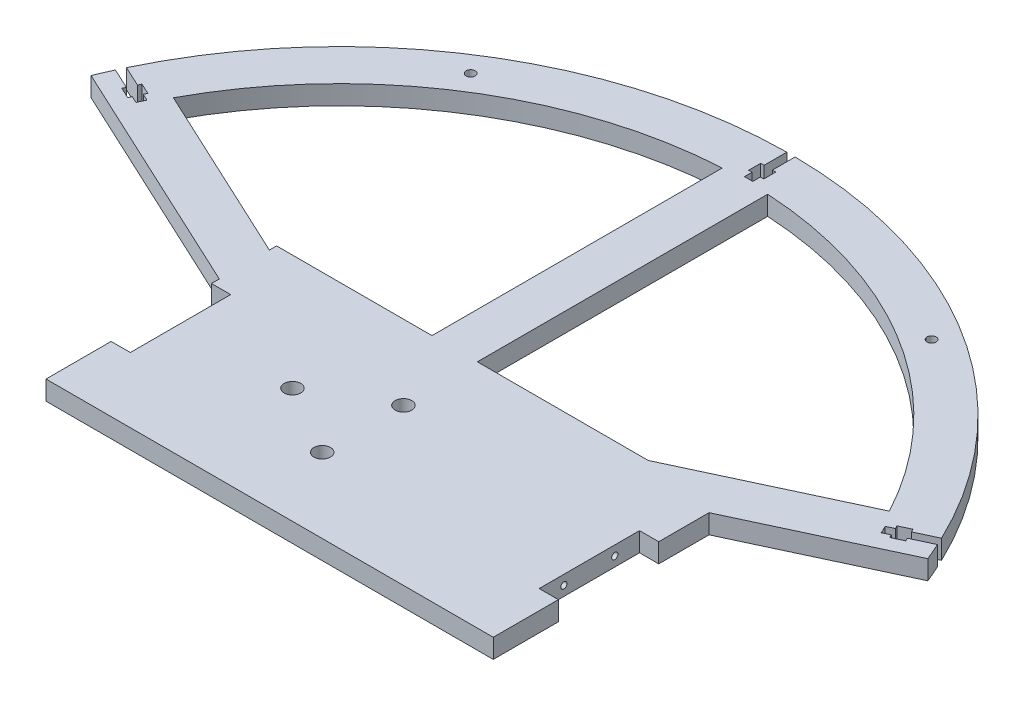
SolidWorks part; units mm, degrees
material "6061 Alloy"
ref_plane "Front Plane" through (0, 0, 0) normal (0, 0, 1) x (1, 0, 0)
ref_plane "Top Plane" through (0, 0, 0) normal (0, 1, 0) x (1, 0, 0)
ref_plane "Right Plane" through (0, 0, 0) normal (1, 0, 0) x (0, 0, -1)
sketch "Sketch1" plane through (0, 0, 0) normal (0, 1, 0) x (1, 0, 0)
  line L0 (0, 0) -> (0, 149.238) construction
  line L1 (0, 0) -> (135.2556, 63.0707) construction
  line L2 (0, 0) -> (-135.2556, 63.0707) construction
  line L3 (3.1696, 6.7973) -> (-132.0859, 69.868)
  line L4 (7.5, 0) -> (7.5, 149.238)
  line L5 (3.1696, -6.7973) -> (138.4252, 56.2734)
  line L6 (-3.1696, -6.7973) -> (-138.4252, 56.2734)
  line L7 (-7.5, 0) -> (-7.5, 149.238)
  line L8 (-3.1696, 6.7973) -> (132.0859, 69.868)
  line L10 (-58.85, -38.1) -> (88.95, -38.1)
  line L11 (-58.85, -38.1) -> (-58.85, 38.1)
  line L12 (-58.85, 38.1) -> (88.95, 38.1)
  line L13 (88.95, -38.1) -> (88.95, 38.1)
  line L14 (-58.85, -38.1) -> (88.95, 38.1) construction
  line L15 (-58.85, 38.1) -> (88.95, -38.1) construction
  circle A0 centre (0, 0) radius 150 construction
  circle A1 centre (0, 0) radius 149.238
  circle A2 centre (0, 0) radius 134.238
  circle A3 centre (0, 0) radius 14
  point P7 (0, 0)
  point P11 (0, 0)
  dimension "D1" = 150
  dimension "D2" = 0.762
  dimension "D3" = 15
  dimension "D10" = 28
  dimension "D4" = 65
  dimension "D5" = 65
  dimension "D8" = 147.8
  dimension "D9" = 76.2
  dimension "D11" = 58.85
  dimension "D12" = 38.1
  dimension "D6" = 7.5
  dimension "D7" = 7.5
extrude "Boss-Extrude1" add sketch "Sketch1" along normal mid plane 6.35
sketch "Sketch2" plane through (0, 0, 0) normal (0, 1, 0) x (1, 0, 0)
  line L0 (-1.375, 135.238) -> (-1.375, 149.238)
  line L1 (-1.375, 135.238) -> (1.375, 135.238)
  line L2 (-1.375, 149.238) -> (1.375, 149.238)
  line L3 (1.375, 135.238) -> (1.375, 149.238)
  line L4 (-1.375, 135.238) -> (1.375, 149.238) construction
  line L5 (-1.375, 149.238) -> (1.375, 135.238) construction
  line L6 (-2.5, 137.738) -> (-2.5, 141.738)
  line L7 (-2.5, 137.738) -> (2.5, 137.738)
  line L8 (-2.5, 141.738) -> (2.5, 141.738)
  line L9 (2.5, 137.738) -> (2.5, 141.738)
  line L10 (-2.5, 137.738) -> (2.5, 141.738) construction
  line L11 (-2.5, 141.738) -> (2.5, 137.738) construction
  line L12 (0, -1000) -> (0, 49000) construction
  line L13 (-1000, 0) -> (49000, 0) construction
  arc A1 (138.2543, 56.1937) -> (-138.2543, 56.1937) centre (0, 0) ccw construction
  point P1 (0, 142.238)
  point P2 (0, 139.738)
  dimension "D1" = 2.75
  dimension "D2" = 14
  dimension "D3" = 4
  dimension "D4" = 5
  dimension "D5" = 2.5
extrude "Cut-Extrude1" cut sketch "Sketch2" against normal through all both and the other way through all contours L7 L0 L1 L3 | L8 L0 L7 L3 | L7 L9 L8 L3 | L0 L8 L3 L2 | L8 L6 L7 L0
pattern_circular "CirPattern1" count 2 every 65 about axis through (0, 0, 0) along (0, 1, 0) of "Cut-Extrude1"
hole_wizard "Ø3.0 (3) Diameter Hole1" positions "Sketch3" profile "Sketch4" hole size "Ø3.0" standard "ANSI Metric" end condition up to next
sketch "Sketch3" plane through (0, 3.175, 0) normal (0, 1, 0) x (1, 0, 0)
  line L11 (0, 0) -> (-80.1855, 125.8661) construction
  line L13 (0, 0) -> (80.1855, 125.8661) construction
  line L16 (-48.85, -28.1) -> (78.95, -28.1)
  line L17 (-48.85, -28.1) -> (-48.85, 28.1)
  line L18 (-48.85, 28.1) -> (78.95, 28.1)
  line L19 (78.95, -28.1) -> (78.95, 28.1)
  line L20 (-48.85, -28.1) -> (78.95, 28.1) construction
  line L21 (-48.85, 28.1) -> (78.95, -28.1) construction
  line L24 (80.1855, 125.8661) -> (72.126, 113.2152)
  line L26 (-80.1855, 125.8661) -> (-72.126, 113.2152)
  line L32 (88.95, -38.1) -> (88.95, 33.2027) construction
  line L33 (-58.85, -38.1) -> (88.95, -38.1) construction
  line L34 (-58.85, -38.1) -> (-58.85, 19.1669) construction
  line L35 (-58.85, 38.1) -> (-7.5, 38.1) construction
  arc A14 (-1.375, 149.2317) -> (-134.6687, 64.3142) centre (0, 0) ccw construction
  arc A15 (-7.5, 134.0283) -> (-118.3013, 63.4401) centre (0, 0) ccw construction
  arc A16 (134.6687, 64.3142) -> (1.375, 149.2317) centre (0, 0) ccw construction
  arc A17 (118.3013, 63.4401) -> (7.5, 134.0283) centre (0, 0) ccw construction
  point P605 (-76.1558, 119.5406)
  point P607 (76.1558, 119.5406)
  dimension "D1" = 10
  dimension "D2" = 10
  dimension "D3" = 10
  dimension "D4" = 10
sketch "Sketch4" plane through (76.1558, 3.175, -119.5406) normal (1, 0, 0) x (0, 0, 1)
  line L0 (0, 0) -> (0, 6.35)
  line L1 (0, 6.35) -> (1.5, 6.35)
  line L2 (1.5, 6.35) -> (1.5, 0)
  line L5 (1.5, 0) -> (0, 0)
  line L11 (0, -6.35) -> (0, 107.95) construction
  dimension "Thru Hole Dia." = 3
  dimension "Thru Hole Depth" = 6.35
hole_wizard "Ø8.0 (8) Diameter Hole1" positions "Sketch5" profile "Sketch6" hole size "Ø8.0" standard "ANSI Metric"
sketch "Sketch5" plane through (0, 3.175, 0) normal (0, 1, 0) x (1, 0, 0)
  point P0 (0, 0)
sketch "Sketch6" plane through (0, 3.175, 0) normal (1, 0, 0) x (0, 0, 1)
  line L0 (0, 0) -> (0, 6.35)
  line L1 (0, 6.35) -> (4, 6.35)
  line L2 (4, 6.35) -> (4, 0)
  line L5 (4, 0) -> (0, 0)
  line L11 (0, -6.35) -> (0, 107.95) construction
  dimension "Thru Hole Dia." = 8
  dimension "Thru Hole Depth" = 6.35
hole_wizard "M5 Clearance Hole1" positions "Sketch7" profile "Sketch8" hole size "M5" standard "ANSI Metric" end condition up to next
sketch "Sketch7" plane through (0, 3.175, 0) normal (0, 1, 0) x (1, 0, 0)
  point P201 (-15.5, 0)
  point P209 (7.75, 13.4234)
  point P210 (7.75, -13.4234)
  dimension "D1" = 15.5
  dimension "D2" = 3
sketch "Sketch8" plane through (-15.5, 3.175, 0) normal (1, 0, 0) x (0, 0, 1)
  line L0 (0, 0) -> (0, 6.35)
  line L1 (0, 6.35) -> (2.75, 6.35)
  line L2 (2.75, 6.35) -> (2.75, 0)
  line L5 (2.75, 0) -> (0, 0)
  line L11 (0, -6.35) -> (0, 107.95) construction
  dimension "Thru Hole Dia." = 5.5
  dimension "Thru Hole Depth" = 6.35
sketch "Sketch9" plane through (0, 3.175, 0) normal (0, 1, 0) x (1, 0, 0)
  line L0 (-58.85, -16.58) -> (-52.5, -16.58)
  line L1 (-58.85, -16.58) -> (-58.85, 16.58)
  line L2 (-52.5, -16.58) -> (-52.5, 16.58)
  line L3 (-58.85, 16.58) -> (-52.5, 16.58)
  line L4 (-58.85, -38.1) -> (-58.85, 19.1669) construction
  line L5 (88.95, -16.58) -> (82.6, -16.58)
  line L6 (88.95, -16.58) -> (88.95, 16.58)
  line L7 (82.6, -16.58) -> (82.6, 16.58)
  line L8 (88.95, 16.58) -> (82.6, 16.58)
  line L9 (88.95, -38.1) -> (88.95, 33.2027) construction
  point P12 (-52.5, 0)
  point P14 (82.6, 0)
  dimension "D1" = 33.16
  dimension "D2" = 6.35
  dimension "D3" = 33.16
  dimension "D4" = 6.35
extrude "Cut-Extrude2" cut sketch "Sketch9" against normal through all
hole_wizard "M2.5x0.45 Tapped Hole1" positions "Sketch10" profile "Sketch11" tap size "M2.5x0.45" standard "ANSI Metric"
sketch "Sketch10" plane through (-52.5, 0, 0) normal (-1, 0, 0) x (0, 0, 1)
  point P0 (-8.415, 0)
  point P2 (8.415, 0)
  dimension "D1" = 8.415
  dimension "D2" = 8.415
sketch "Sketch11" plane through (-52.5, 0, -8.415) normal (0, 1, 0) x (0, 0, 1)
  line L0 (0, 0) -> (0, 6.9659)
  line L1 (0, 6.9659) -> (1.025, 6.35)
  line L2 (1.025, 6.35) -> (1.025, 0)
  line L5 (1.025, 0) -> (0, 0)
  line L10 (0, 6.9659) -> (-1.025, 6.35) construction
  line L11 (0, -6.35) -> (0, 107.95) construction
  dimension "Tap Drill Dia." = 2.05
  dimension "Tap Drill Depth" = 6.35
  dimension "Drill Angle" = 118
cosmetic thread "Hole Thread5" parameters "D1"=5, "D2"=2.5
cosmetic thread "Hole Thread6" parameters "D1"=5, "D2"=2.5
ref_plane "Plane1" through (15.05, 0, 0) normal (-1, 0, 0) x (0, 0, 1)
mirror "Mirror1" about plane through (15.05, 0, 0) normal (-1, 0, 0) of "M2.5x0.45 Tapped Hole1"
cosmetic thread "Hole Thread7" parameters "D1"=5, "D2"=2.5
cosmetic thread "Hole Thread8" parameters "D1"=5, "D2"=2.5
